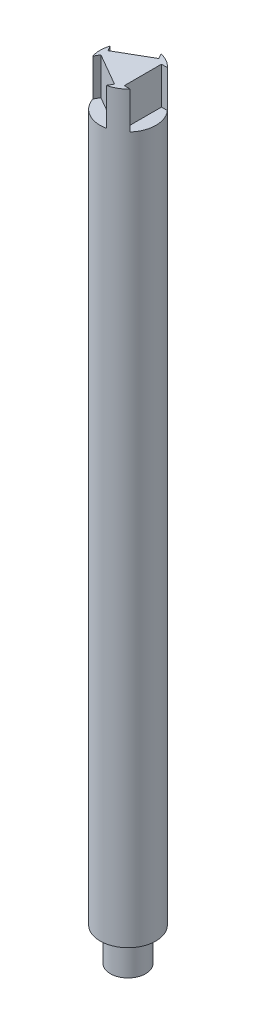
SolidWorks part; units mm, degrees
ref_plane "Front Plane" through (0, 0, 0) normal (0, 0, 1) x (1, 0, 0)
ref_plane "Top Plane" through (0, 0, 0) normal (0, 1, 0) x (1, 0, 0)
ref_plane "Right Plane" through (0, 0, 0) normal (1, 0, 0) x (0, 0, -1)
sketch "Sketch1" plane through (0, 0, 0) normal (0, 1, 0) x (1, 0, 0)
  circle A0 centre (0, 0) radius 4.75
  dimension "D1" = 9.5
extrude "Boss-Extrude1" add sketch "Sketch1" along normal blind 9
sketch "Sketch2" plane through (0, 9, 0) normal (0, 1, 0) x (1, 0, 0)
  circle A0 centre (0, 0) radius 7.5
  dimension "D1" = 15
extrude "Boss-Extrude2" add sketch "Sketch2" along normal blind 200
sketch "Sketch3" plane through (0, 0, 0) normal (1, 0, 0) x (0, 0, -1)
  line L0 (7.5, 209) -> (-7.5, 209) construction
  line L1 (-5, 199) -> (5, 199)
  line L2 (-5, 199) -> (-5, 209)
  line L3 (-5, 209) -> (5, 209)
  line L4 (5, 199) -> (5, 209)
  line L5 (-5, 199) -> (5, 209) construction
  line L6 (-5, 209) -> (5, 199) construction
  point P0 (0, 204)
  dimension "D1" = 10
  dimension "D2" = 10
extrude "Cut-Extrude1" cut sketch "Sketch3" along normal through all from offset 4
pattern_circular "CirPattern2" count 3 over 360 about axis through (0, 0, 0) along (0, 1, 0) of "Cut-Extrude1"
